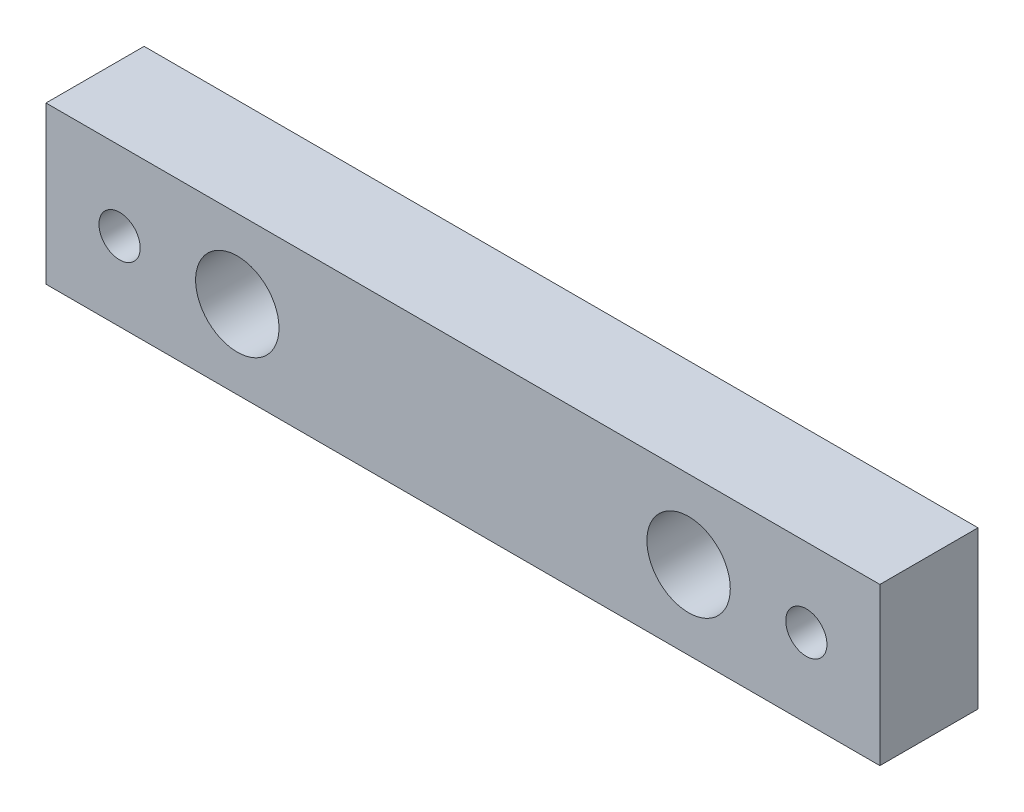
SolidWorks part; units mm, degrees
ref_plane "Front" through (0, 0, 0) normal (0, 0, 1) x (1, 0, 0)
ref_plane "Top" through (0, 0, 0) normal (0, 1, 0) x (1, 0, 0)
ref_plane "Right" through (0, 0, 0) normal (1, 0, 0) x (0, 0, -1)
sketch "草图1" plane through (0, 0, 0) normal (0, 0, 1) x (1, 0, 0)
  line L0 (0, 0) -> (23, 0) construction
  line L1 (42.5, 8) -> (-42.5, 8)
  line L2 (42.5, 8) -> (42.5, -8)
  line L3 (42.5, -8) -> (-42.5, -8)
  line L4 (-42.5, 8) -> (-42.5, -8)
  line L5 (42.5, 8) -> (-42.5, -8) construction
  line L6 (42.5, -8) -> (-42.5, 8) construction
  line L7 (0, 0) -> (-23, 0) construction
  circle A0 centre (-23, 0) radius 4.25
  circle A1 centre (23, 0) radius 4.25
  point P0 (0, 0)
  dimension "D1" = 8.5
  dimension "D5" = 8.5
  dimension "D2" = 23
  dimension "D3" = 85
  dimension "D4" = 23
  dimension "D6" = 16
extrude "凸台-拉伸1" add sketch "草图1" along normal blind 10
sketch "草图2" plane through (0, 0, 10) normal (0, 0, 1) x (1, 0, 0)
  line L0 (0, 8) -> (0, 0) construction
  line L1 (42.5, 8) -> (-42.5, 8) construction
  line L2 (0, 0) -> (35, 0) construction
  circle A0 centre (35, 0) radius 2.5
  circle A1 centre (-35, 0) radius 2.5
  dimension "D2" = 5
  dimension "D1" = 35
hole_wizard "M5 螺纹孔1" positions "草图3" profile "草图4" tap size "M5" standard "GB"
sketch "草图3" plane through (0, 0, 10) normal (0, 0, 1) x (1, 0, 0)
  point P0 (-35, 0)
  point P3 (35, 0)
sketch "草图4" plane through (-35, 0, 10) normal (1, 0, 0) x (0, -1, 0)
  line L0 (0, 0) -> (0, 16.1618)
  line L1 (0, 16.1618) -> (2.1, 14.9)
  line L2 (2.1, 14.9) -> (2.1, 0)
  line L5 (2.1, 0) -> (0, 0)
  line L10 (0, 16.1618) -> (-2.1, 14.9) construction
  line L11 (0, -6.35) -> (0, 107.95) construction
  dimension "螺纹孔钻头直径" = 4.2
  dimension "螺纹孔钻头深度" = 14.9
  dimension "导头角度" = 118
cosmetic thread "孔螺蚊线1" parameters "D1"=10, "D2"=5
cosmetic thread "孔螺蚊线2" parameters "D1"=10, "D2"=5
